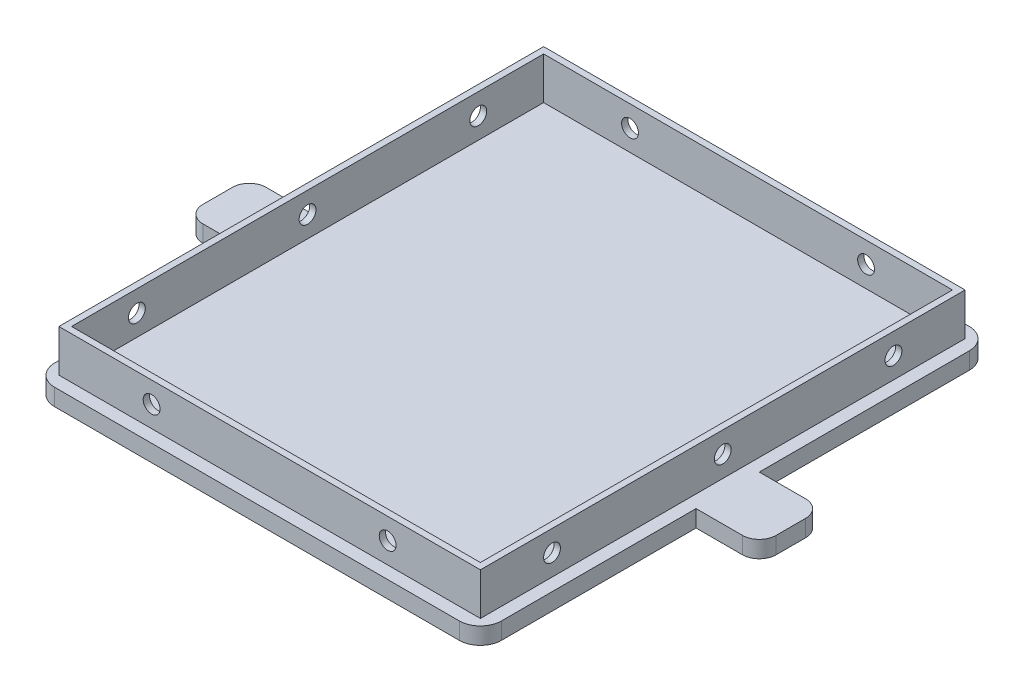
SolidWorks part; units mm, degrees
ref_plane "Front Plane" through (0, 0, 0) normal (0, 0, 1) x (1, 0, 0)
ref_plane "Top Plane" through (0, 0, 0) normal (0, 1, 0) x (1, 0, 0)
ref_plane "Right Plane" through (0, 0, 0) normal (1, 0, 0) x (0, 0, -1)
sketch "Sketch1" plane through (0, 0, 0) normal (0, 1, 0) x (1, 0, 0)
  line L1 (-53, 60.5) -> (53, 60.5)
  line L2 (-53, 60.5) -> (-53, -60.5)
  line L3 (-53, -60.5) -> (53, -60.5)
  line L4 (53, 60.5) -> (53, -60.5)
  line L5 (-53, 60.5) -> (53, -60.5) construction
  line L6 (-53, -60.5) -> (53, 60.5) construction
  point P0 (0, 0)
  dimension "D1" = 121
  dimension "D2" = 106
extrude "Boss-Extrude1" add sketch "Sketch1" along normal blind 4
sketch "Sketch2" plane through (0, 4, 0) normal (0, 1, 0) x (1, 0, 0)
  line L0 (-53, 60.5) -> (-53, -60.5) construction
  line L1 (-50, 57.5) -> (50, 57.5)
  line L2 (-50, 57.5) -> (-50, -57.5)
  line L3 (-50, -57.5) -> (50, -57.5)
  line L4 (50, 57.5) -> (50, -57.5)
  line L5 (-50, 57.5) -> (50, -57.5) construction
  line L6 (-50, -57.5) -> (50, 57.5) construction
  line L7 (53, 60.5) -> (-53, 60.5) construction
  line L9 (-48.5, 56) -> (48.5, 56)
  line L10 (-48.5, 56) -> (-48.5, -56)
  line L11 (-48.5, -56) -> (48.5, -56)
  line L12 (48.5, 56) -> (48.5, -56)
  line L13 (-48.5, 56) -> (48.5, -56) construction
  line L14 (-48.5, -56) -> (48.5, 56) construction
  point P0 (0, 0)
  point P10 (0, 0)
  dimension "D1" = 3
  dimension "D2" = 3
  dimension "D3" = 1.5
  dimension "D4" = 1.5
extrude "Boss-Extrude2" add sketch "Sketch2" along normal blind 10
sketch "Sketch5" plane through (0, 0, 0) normal (0, -1, 0) x (1, 0, 0)
  line L0 (53, -5.6667) -> (53, 9.3333)
  line L1 (53, 60.5) -> (53, -60.5) construction
  line L2 (53, 9.3333) -> (68, 9.3333)
  line L3 (68, 9.3333) -> (68, -5.6667)
  line L4 (68, -5.6667) -> (53, -5.6667)
  line L8 (-68, -5.6667) -> (-53, -5.6667)
  line L9 (-68, 9.3333) -> (-68, -5.6667)
  line L10 (-53, 9.3333) -> (-68, 9.3333)
  line L11 (-53, -5.6667) -> (-53, 9.3333)
  point P5 (53, 1.8333)
  point P17 (-53, 1.8333)
  dimension "D1" = 15
  dimension "D2" = 15
extrude "Boss-Extrude4" add sketch "Sketch5" against normal up to surface (4 mm away) up to face at (0, 4, 0)
fillet "Fillet1" radius 4 4 edges at (-68, 2, -5.6667) (-68, 2, 9.3333) (68, 2, 9.3333) (68, 2, -5.6667)
sketch "Sketch6" plane through (53, 0, 0) normal (1, 0, 0) x (0, 0, -1)
  line L0 (60.5, 4) -> (60.5, 0) construction
  line L1 (-60.5, 4) -> (-60.5, 0) construction
  line L2 (-57.5, 4) -> (57.5, 4) construction
  circle A0 centre (40.5, 9) radius 2
  circle A1 centre (0, 9) radius 2
  circle A2 centre (-40.5, 9) radius 2
  dimension "D1" = 20
  dimension "D2" = 40.5
  dimension "D3" = 20
  dimension "D4" = 5
  dimension "D5" = 5
extrude "Cut-Extrude1" cut sketch "Sketch6" against normal blind 119
sketch "Sketch7" plane through (0, 0, 60.5) normal (0, 0, 1) x (1, 0, 0)
  line L0 (53, 4) -> (53, 0) construction
  line L1 (-53, 4) -> (53, 4) construction
  line L2 (-53, 4) -> (-53, 0) construction
  circle A0 centre (28, 9) radius 2
  circle A1 centre (-28, 9) radius 2
  point P6 (53, 2)
  dimension "D3" = 25
  dimension "D1" = 25
  dimension "D2" = 5
  dimension "D4" = 5
extrude "Cut-Extrude2" cut sketch "Sketch7" against normal blind 126
fillet "Fillet2" radius 5 4 edges at (-53, 2, -60.5) (53, 2, -60.5) (53, 2, 60.5) (-53, 2, 60.5)
